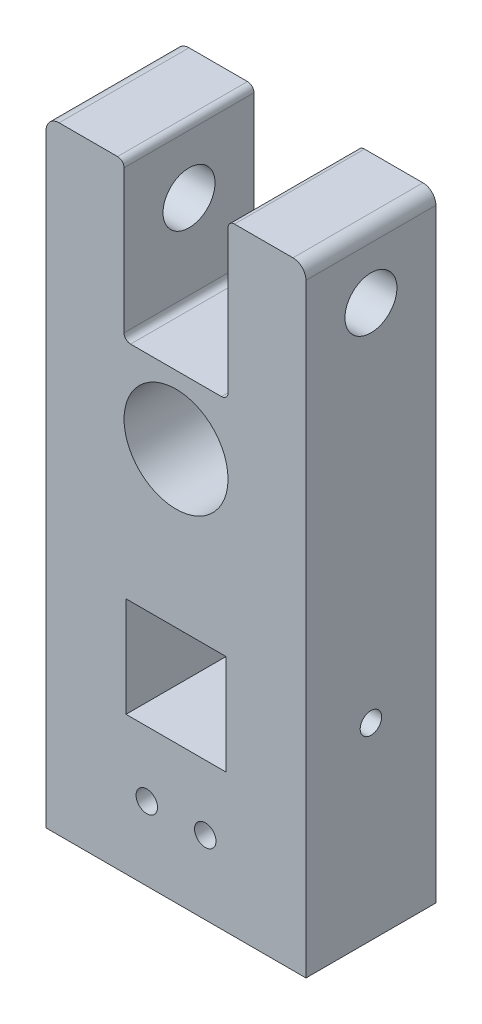
SolidWorks part; units mm, degrees
ref_plane "前视基准面" through (0, 0, 0) normal (0, 0, 1) x (1, 0, 0)
ref_plane "上视基准面" through (0, 0, 0) normal (0, 1, 0) x (1, 0, 0)
ref_plane "右视基准面" through (0, 0, 0) normal (1, 0, 0) x (0, 0, -1)
sketch "草图1" plane through (0, 0, 0) normal (0, 0, 1) x (1, 0, 0)
  line L1 (-20, -34.5) -> (20, -34.5)
  line L2 (-20, -34.5) -> (-20, 34.5)
  line L3 (-20, 34.5) -> (20, 34.5)
  line L4 (20, -34.5) -> (20, 34.5)
  line L5 (-20, -34.5) -> (20, 34.5) construction
  line L6 (-20, 34.5) -> (20, -34.5) construction
  point P0 (0, 0)
  dimension "D1" = 40
  dimension "D2" = 69
extrude "凸台-拉伸1" add sketch "草图1" along normal blind 20
sketch "草图2" plane through (0, 0, 20) normal (0, 0, 1) x (1, 0, 0)
  circle A0 centre (0, 0) radius 8
  dimension "D1" = 16
  dimension "D2" = 0
extrude "切除-拉伸1" cut sketch "草图2" against normal blind 20
sketch "草图3" plane through (0, -34.5, 0) normal (0, -1, 0) x (1, 0, 0)
  line L1 (-20, 0) -> (20, 0)
  line L2 (-20, 0) -> (-20, 20)
  line L3 (-20, 20) -> (20, 20)
  line L4 (20, 0) -> (20, 20)
  line L5 (-20, 0) -> (20, 20) construction
  line L6 (-20, 20) -> (20, 0) construction
  point P0 (0, 10)
extrude "凸台-拉伸2" add sketch "草图3" along normal blind 26
sketch "草图8" plane through (0, 0, 20) normal (0, 0, 1) x (1, 0, 0)
  line L0 (0, 19.6097) -> (0, -97.8311) construction
  line L1 (20, -60.5) -> (-20, -60.5) construction
  line L2 (-7.7, -39.2) -> (7.7, -39.2)
  line L3 (-7.7, -39.2) -> (-7.7, -23.8)
  line L4 (-7.7, -23.8) -> (7.7, -23.8)
  line L5 (7.7, -39.2) -> (7.7, -23.8)
  line L6 (-7.7, -39.2) -> (7.7, -23.8) construction
  line L7 (-7.7, -23.8) -> (7.7, -39.2) construction
  point P3 (0, -31.5)
  dimension "D1" = 15.4
  dimension "D2" = 15.4
  dimension "D3" = 29
extrude "切除-拉伸6" cut sketch "草图8" against normal blind 100
sketch "草图4" plane through (0, 0, 20) normal (0, 0, 1) x (1, 0, 0)
  line L1 (-7.7, -39.2) -> (7.7, -39.2) construction
  line L2 (0, 24.4829) -> (0, -73.983) construction
  circle A0 centre (4.5, -49.2) radius 1.65
  circle A1 centre (-4.5, -49.2) radius 1.65
  dimension "D1" = 3.3
  dimension "D2" = 10
  dimension "D3" = 3.3
  dimension "D4" = 4.5
  dimension "D5" = 4.5
  dimension "D6" = 10
extrude "切除-拉伸2" cut sketch "草图4" against normal blind 40
sketch "草图5" plane through (0, -60.5, 0) normal (0, -1, 0) x (1, 0, 0)
  line L0 (0, 21.447) -> (0, -4.8794) construction
  line L2 (-2.5, 9.5) -> (2.5, 9.5)
  line L3 (-2.5, 9.5) -> (-2.5, 14.5)
  line L4 (-2.5, 14.5) -> (2.5, 14.5)
  line L5 (2.5, 9.5) -> (2.5, 14.5)
  line L6 (-2.5, 9.5) -> (2.5, 14.5) construction
  line L7 (-2.5, 14.5) -> (2.5, 9.5) construction
  line L9 (20, 20) -> (-20, 20) construction
  point P3 (0, 12)
  dimension "D1" = 5
  dimension "D2" = 5
  dimension "D3" = 8
extrude "切除-拉伸3" cut sketch "草图5" against normal blind 6
fillet "圆角1" radius 2 2 edges at (20, 34.5, 10) (-20, 34.5, 10)
sketch "草图6" plane through (0, 0, 20) normal (0, 0, 1) x (1, 0, 0)
  line L0 (0, 35.0308) -> (0, -13.6841) construction
  line L1 (18, 34.5) -> (-18, 34.5) construction
  line L2 (-8, 10.5) -> (8, 10.5)
  line L3 (-8, 10.5) -> (-8, 34.5)
  line L4 (-8, 34.5) -> (8, 34.5)
  line L5 (8, 10.5) -> (8, 34.5)
  line L6 (-8, 10.5) -> (8, 34.5) construction
  line L7 (-8, 34.5) -> (8, 10.5) construction
  point P3 (0, 22.5)
  dimension "D1" = 16
  dimension "D2" = 24
extrude "切除-拉伸4" cut sketch "草图6" against normal blind 50
sketch "草图7" plane through (20, 0, 0) normal (1, 0, 0) x (0, 0, -1)
  line L0 (-10, 32.5) -> (-10, -85.9367) construction
  line L1 (0, 32.5) -> (-20, 32.5) construction
  line L2 (-20, 34.5) -> (0, 34.5) construction
  circle A0 centre (-10, 24.5) radius 4
  dimension "D1" = 10
  dimension "D2" = 8
extrude "切除-拉伸5" cut sketch "草图7" against normal blind 100
fillet "圆角2" radius 1 4 edges at (8, 34.5, 10) (-8, 34.5, 10) (8, 10.5, 10) (-8, 10.5, 10)
sketch "草图9" plane through (20, 0, 0) normal (1, 0, 0) x (0, 0, -1)
  line L0 (-10, -60.5) -> (-10, 0) construction
  line L1 (0, -60.5) -> (-20, -60.5) construction
  circle A0 centre (-10, -31.5) radius 1.65
  dimension "D2" = 3.3
  dimension "D1" = 29
extrude "切除-拉伸7" cut sketch "草图9" against normal blind 1000
